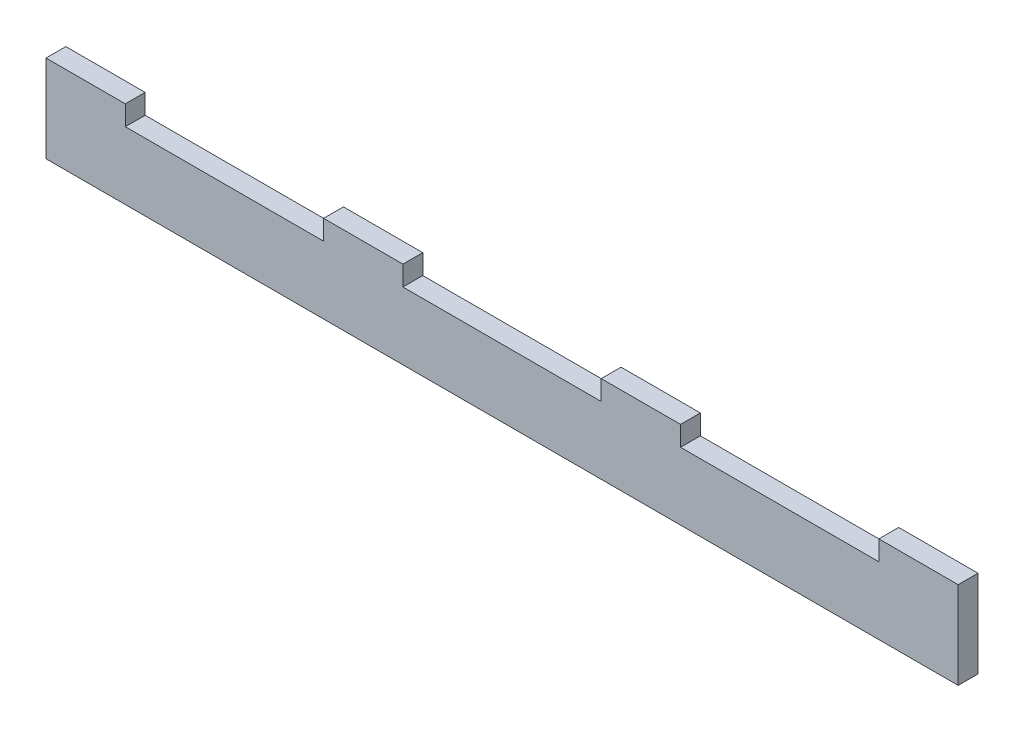
SolidWorks part; units mm, degrees
ref_plane "Plan de face" through (0, 0, 0) normal (0, 0, 1) x (1, 0, 0)
ref_plane "Plan de dessus" through (0, 0, 0) normal (0, 1, 0) x (1, 0, 0)
ref_plane "Plan de droite" through (0, 0, 0) normal (1, 0, 0) x (0, 0, -1)
sketch "Esquisse1" plane through (0, 0, 0) normal (0, 0, 1) x (1, 0, 0)
  line L0 (0, 0) -> (230, 0)
  line L1 (230, 0) -> (230, 22)
  line L2 (230, 22) -> (210, 22)
  line L3 (210, 22) -> (210, 17)
  line L4 (210, 17) -> (160, 17)
  line L5 (160, 17) -> (160, 22)
  line L6 (160, 22) -> (140, 22)
  line L7 (140, 22) -> (140, 17)
  line L8 (140, 17) -> (90, 17)
  line L9 (90, 17) -> (90, 22)
  line L10 (90, 22) -> (70, 22)
  line L11 (70, 22) -> (70, 17)
  line L12 (70, 17) -> (20, 17)
  line L13 (20, 17) -> (20, 22)
  line L14 (20, 22) -> (0, 22)
  line L19 (0, 22) -> (0, 0)
extrude "Boss.-Extru.2" add sketch "Esquisse1" along normal blind 5 contours L19 L0 L1 L2 L3 L4 L5 L6 L7 L8 L9 L10 L11 L12 L13 L14
